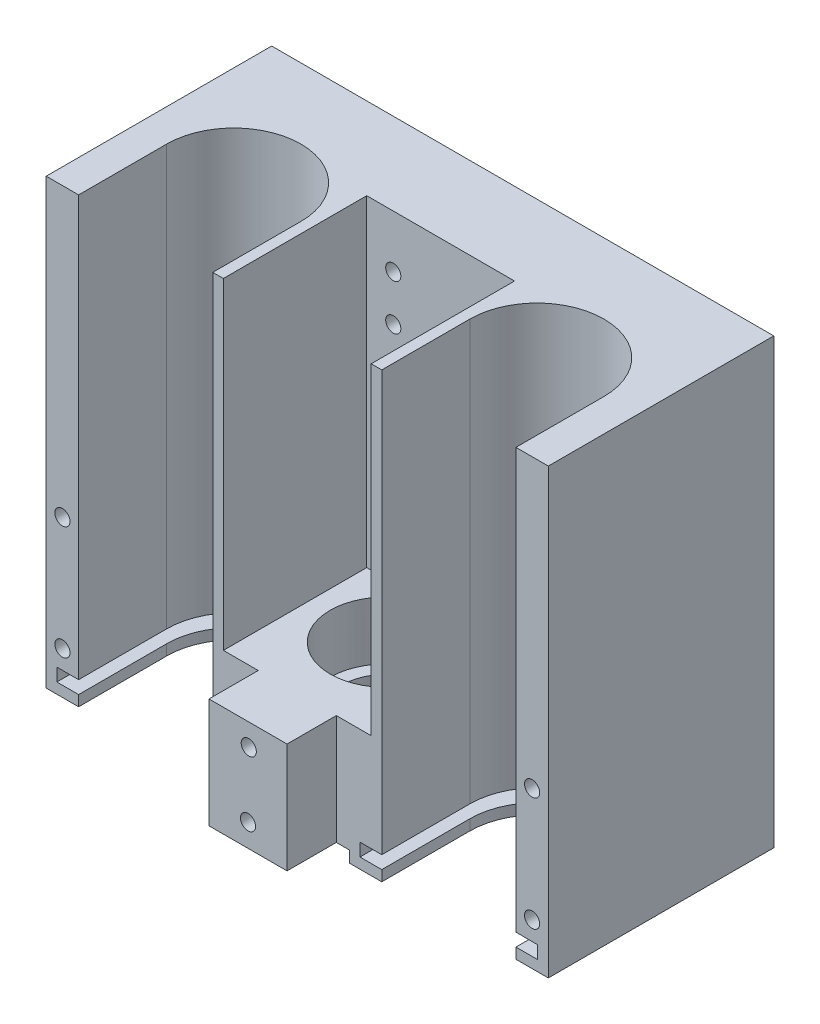
SolidWorks part; units mm, degrees
ref_plane "Płaszczyzna przednia" through (0, 0, 0) normal (0, 0, 1) x (1, 0, 0)
ref_plane "Płaszczyzna górna" through (0, 0, 0) normal (0, 1, 0) x (1, 0, 0)
ref_plane "Płaszczyzna prawa" through (0, 0, 0) normal (1, 0, 0) x (0, 0, -1)
sketch "Sketch1" plane through (0, 0, 0) normal (0, 0, 1) x (1, 0, 0)
  line L1 (-66.25, 58.5) -> (66.25, 58.5)
  line L2 (-66.25, 58.5) -> (-66.25, -58.5)
  line L3 (-66.25, -58.5) -> (66.25, -58.5)
  line L4 (66.25, 58.5) -> (66.25, -58.5)
  line L5 (-66.25, 58.5) -> (66.25, -58.5) construction
  line L6 (-66.25, -58.5) -> (66.25, 58.5) construction
  point P4 (0, 0)
  dimension "D1" = 117
  dimension "D2" = 132.5
extrude "Boss-Extrude1" add sketch "Sketch1" along normal blind 55.25
sketch "Sketch2" plane through (0, 58.5, 0) normal (0, 1, 0) x (1, 0, 0)
  line L0 (66.25, 0) -> (-66.25, 0) construction
  line L1 (-66.25, -55.25) -> (-66.25, 0) construction
  line L2 (-57.7, -32) -> (-57.7, -55.25)
  line L3 (-22.3, -32) -> (-22.3, -55.25)
  line L4 (66.25, -55.25) -> (-66.25, -55.25) construction
  line L5 (-57.7, -55.25) -> (-22.3, -55.25)
  line L6 (0, -55) -> (0, 55) construction
  line L7 (57.7, -32) -> (57.7, -55.25)
  line L8 (22.3, -32) -> (22.3, -55.25)
  line L9 (57.7, -55.25) -> (22.3, -55.25)
  arc A0 (-22.3, -32) -> (-57.7, -32) centre (-40, -32) ccw
  arc A1 (22.3, -32) -> (57.7, -32) centre (40, -32) cw
  dimension "D3" = 35.4
  dimension "D1" = 32
  dimension "D2" = 26.25
  dimension "D6" = 44.6
extrude "Cut-Extrude1" cut sketch "Sketch2" against normal up to next contours L7 L9 L8 A1 | L5 L3 A0 L2
sketch "Sketch3" plane through (0, 58.5, 0) normal (0, 1, 0) x (1, 0, 0)
  line L0 (22.3, -55.25) -> (-22.3, -55.25) construction
  line L1 (-19.5, -17.42) -> (19.5, -17.42)
  line L2 (-19.5, -17.42) -> (-19.5, -55.25)
  line L3 (-19.5, -55.25) -> (19.5, -55.25)
  line L4 (19.5, -17.42) -> (19.5, -55.25)
  line L5 (0, -55.25) -> (0, -17.42) construction
  line L6 (-19.5, -36.335) -> (19.5, -36.335) construction
  point P152 (0, -36.335)
  dimension "D1" = 39
  dimension "D2" = 37.83
  dimension "D3" = 115.4
extrude "Cut-Extrude2" cut sketch "Sketch3" against normal blind 85
sketch "Sketch4" plane through (0, -26.5, 0) normal (0, 1, 0) x (1, 0, 0)
  line L0 (-19.5, -55.25) -> (19.5, -55.25) construction
  line L1 (-10.3, -55.25) -> (10.3, -55.25)
  line L2 (-10.3, -55.25) -> (-10.3, -68.25)
  line L3 (-10.3, -68.25) -> (10.3, -68.25)
  line L4 (10.3, -55.25) -> (10.3, -68.25)
  line L5 (0, -68.25) -> (0, -55.25) construction
  line L6 (-10.3, -61.75) -> (10.3, -61.75) construction
  point P180 (0, -61.75)
  dimension "D1" = 20.6
  dimension "D2" = 13
  dimension "D3" = 44.6
extrude "Boss-Extrude2" add sketch "Sketch4" against normal up to surface (32 mm away) up to face at (0, -58.5, 35.3417)
sketch "Sketch5" plane through (0, -58.5, 0) normal (0, -1, 0) x (1, 0, 0)
  line L0 (-66.25, 0) -> (66.25, 0) construction
  line L1 (13.75, 0) -> (-13.75, 0)
  line L2 (13.75, 0) -> (13.75, 68.25)
  line L3 (13.75, 68.25) -> (-13.75, 68.25)
  line L4 (-13.75, 0) -> (-13.75, 68.25)
  line L5 (0, 68.25) -> (0, 0) construction
  line L6 (13.75, 34.125) -> (-13.75, 34.125) construction
  line L7 (10.3, 68.25) -> (-10.3, 68.25) construction
  point P260 (0, 34.125)
  dimension "D1" = 27.5
  dimension "D2" = 44.6
extrude "Cut-Extrude3" cut sketch "Sketch5" against normal blind 3
sketch "Sketch6" plane through (0, 0, 55.25) normal (0, 0, 1) x (1, 0, 0)
  line L0 (-66.25, -58.5) -> (-57.7, -58.5) construction
  line L1 (-63.45, -52.3) -> (-16.55, -52.3)
  line L2 (-63.45, -52.3) -> (-63.45, -55.7)
  line L3 (-63.45, -55.7) -> (-16.55, -55.7)
  line L4 (-16.55, -52.3) -> (-16.55, -55.7)
  line L5 (-40, -55.7) -> (-40, -52.3) construction
  line L6 (-63.45, -54) -> (-16.55, -54) construction
  line L7 (16.55, -52.3) -> (63.45, -52.3)
  line L8 (16.55, -52.3) -> (16.55, -55.7)
  line L9 (16.55, -55.7) -> (63.45, -55.7)
  line L10 (63.45, -52.3) -> (63.45, -55.7)
  line L11 (40, -55.7) -> (40, -52.3) construction
  line L12 (16.55, -54) -> (63.45, -54) construction
  line L13 (-66.25, 58.5) -> (-66.25, -58.5) construction
  line L14 (66.25, -58.5) -> (66.25, 58.5) construction
  point P164 (-40, -54)
  point P229 (40, -54)
  dimension "D1" = 46.9
  dimension "D2" = 3.4
  dimension "D3" = 2.8
  dimension "D4" = 2.8
  dimension "D5" = 2.8
  dimension "D6" = 46.9
extrude "Cut-Extrude4" cut sketch "Sketch6" against normal blind 46.9
sketch "Sketch8" plane through (0, -55.5, 0) normal (0, -1, 0) x (1, 0, 0)
  line L0 (0, 0) -> (0, 68.25) construction
  line L1 (-10.3, 68.25) -> (10.3, 68.25) construction
  line L2 (-13.75, 0) -> (13.75, 0) construction
  circle A0 centre (0, 7) radius 4.2
  circle A2 centre (0, 57) radius 4.2
  circle A3 centre (0, 32) radius 4.5
  dimension "D1" = 8.4
  dimension "D2" = 7
  dimension "D4" = 9
  dimension "D5" = 25
  dimension "D3" = 57
extrude "Cut-Extrude5" cut sketch "Sketch8" against normal blind 14
sketch "Sketch9" plane through (0, -26.5, 0) normal (0, 1, 0) x (1, 0, 0)
  circle A0 centre (0, -32) radius 4.5 construction
  circle A1 centre (0, -32) radius 4.5 construction
  circle A2 centre (0, -32) radius 14.58
  dimension "D1" = 29.16
extrude "Cut-Extrude6" cut sketch "Sketch9" against normal blind 15.3
sketch "Sketch10" plane through (0, -41.8, 0) normal (0, 1, 0) x (1, 0, 0)
  circle A0 centre (0, -32) radius 11.2
  dimension "D1" = 22.4
extrude "Cut-Extrude7" cut sketch "Sketch10" against normal blind 7.22
sketch "Sketch11" plane through (0, 0, 68.25) normal (0, 0, 1) x (1, 0, 0)
  line L0 (-10.3, -55.5) -> (10.3, -55.5) construction
  line L3 (10.3, -55.5) -> (10.3, -26.5) construction
  circle A0 centre (0, -49.5) radius 1.75
  point P0 (0, -49.5)
  dimension "D1" = 6
  dimension "D2" = 3.5
  dimension "D3" = 10.3
hole_wizard "Ø3.5 (3.5) Diameter Hole1" positions "Sketch11" profile "Sketch12" hole size "Ø3.5" standard "DIN"
sketch "Sketch12" plane through (0, -49.5, 68.25) normal (1, 0, 0) x (0, -1, 0)
  line L0 (0, 0) -> (0, 21.0515)
  line L1 (0, 21.0515) -> (1.75, 20)
  line L2 (1.75, 20) -> (1.75, 0)
  line L5 (1.75, 0) -> (0, 0)
  line L10 (0, 21.0515) -> (-1.75, 20) construction
  line L11 (0, -6.35) -> (0, 107.95) construction
  dimension "Hole Dia." = 3.5
  dimension "Hole Depth" = 20
  dimension "Drill Angle" = 118
sketch "Sketch14" plane through (0, 0, 0) normal (0, 0, -1) x (-1, 0, 0)
  line L8 (-66.25, -58.5) -> (-13.75, -58.5)
  line L9 (-13.75, -58.5) -> (-13.75, -55.5)
  line L10 (-13.75, -55.5) -> (13.75, -55.5)
  line L11 (13.75, -55.5) -> (13.75, -58.5)
  line L12 (13.75, -58.5) -> (66.25, -58.5)
  line L13 (66.25, -58.5) -> (66.25, 58.5)
  line L14 (66.25, 58.5) -> (-66.25, 58.5)
  line L15 (-66.25, 58.5) -> (-66.25, -58.5)
  line L16 (-66.25, -58.5) -> (-13.75, -58.5)
  line L17 (-13.75, -58.5) -> (-13.75, -55.5)
  line L18 (-13.75, -55.5) -> (13.75, -55.5)
  line L19 (13.75, -55.5) -> (13.75, -58.5)
  line L20 (13.75, -58.5) -> (66.25, -58.5)
  line L21 (66.25, -58.5) -> (66.25, 58.5)
  line L22 (66.25, 58.5) -> (-66.25, 58.5)
  line L23 (-66.25, 58.5) -> (-66.25, -58.5)
  dimension "D1" = 0
extrude "Boss-Extrude3" add sketch "Sketch14" along normal blind 4.25
sketch "Sketch15" plane through (0, 0, 68.25) normal (0, 0, 1) x (1, 0, 0)
  circle A0 centre (0, -49.5) radius 2
  dimension "D1" = 4
extrude "Cut-Extrude8" cut sketch "Sketch15" against normal up to next
ref_plane "Plane1" through (0, 0, 32) normal (0, 0, 1) x (1, 0, 0)
mirror "Mirror1" about plane through (0, 0, 32) normal (0, 0, 1) of "Ø3.5 (3.5) Diameter Hole1", "Cut-Extrude8"
sketch "Sketch16" plane through (0, 0, 17.42) normal (0, 0, 1) x (1, 0, 0)
  point P0 (-12.5, 32.58)
  point P1 (12.5, 32.58)
  point P3 (12.5, 44.58)
  point P5 (-12.5, 44.58)
hole_wizard "Ø4.0 mm Dowel Holes1" positions "Sketch16" profile "Sketch17" hole size "Ø4.0" standard "DIN" end condition up to next
sketch "Sketch17" plane through (-12.5, 32.58, 17.42) normal (1, 0, 0) x (0, -1, 0)
  line L0 (0, 0) -> (0, 21.67)
  line L1 (0, 21.67) -> (2, 21.67)
  line L2 (2, 21.67) -> (2, 0)
  line L5 (2, 0) -> (0, 0)
  line L11 (0, -6.35) -> (0, 107.95) construction
  dimension "Thru Hole Dia." = 4
  dimension "Thru Hole Depth" = 21.67
sketch "Sketch18" plane through (0, 0, 55.25) normal (0, 0, 1) x (1, 0, 0)
  line L0 (63.45, -52.3) -> (57.7, -52.3) construction
  line L1 (57.7, -47.3) -> (66.25, -47.3) construction
  line L2 (57.7, -52.3) -> (57.7, 58.5) construction
  line L3 (66.25, -58.5) -> (66.25, 58.5) construction
  point P0 (61.975, -47.3)
  point P9 (61.975, -17.3)
  dimension "D1" = 5
  dimension "D2" = 30
hole_wizard "Ø4.0 mm Dowel Holes2" positions "Sketch18" profile "Sketch19" hole size "Ø4.0" standard "DIN"
sketch "Sketch19" plane through (61.975, -47.3, 55.25) normal (1, 0, 0) x (0, -1, 0)
  line L0 (0, 0) -> (0, 11.2017)
  line L1 (0, 11.2017) -> (2, 10)
  line L2 (2, 10) -> (2, 0)
  line L5 (2, 0) -> (0, 0)
  line L10 (0, 11.2017) -> (-2, 10) construction
  line L11 (0, -6.35) -> (0, 107.95) construction
  dimension "Hole Dia." = 4
  dimension "Hole Depth" = 10
  dimension "Drill Angle" = 118
mirror "Mirror2" about plane through (0, 0, 0) normal (1, 0, 0) of "Ø4.0 mm Dowel Holes2"
sketch "Sketch20" plane through (0, 0, 68.25) normal (0, 0, 1) x (1, 0, 0)
  point P0 (0.2, -32.3)
hole_wizard "Ø4.0 mm Dowel Holes3" positions "Sketch20" profile "Sketch21" hole size "Ø4.0" standard "DIN"
sketch "Sketch21" plane through (0.2, -32.3, 68.25) normal (1, 0, 0) x (0, -1, 0)
  line L0 (0, 0) -> (0, 11.2017)
  line L1 (0, 11.2017) -> (2, 10)
  line L2 (2, 10) -> (2, 0)
  line L5 (2, 0) -> (0, 0)
  line L10 (0, 11.2017) -> (-2, 10) construction
  line L11 (0, -6.35) -> (0, 107.95) construction
  dimension "Hole Dia." = 4
  dimension "Hole Depth" = 10
  dimension "Drill Angle" = 118
